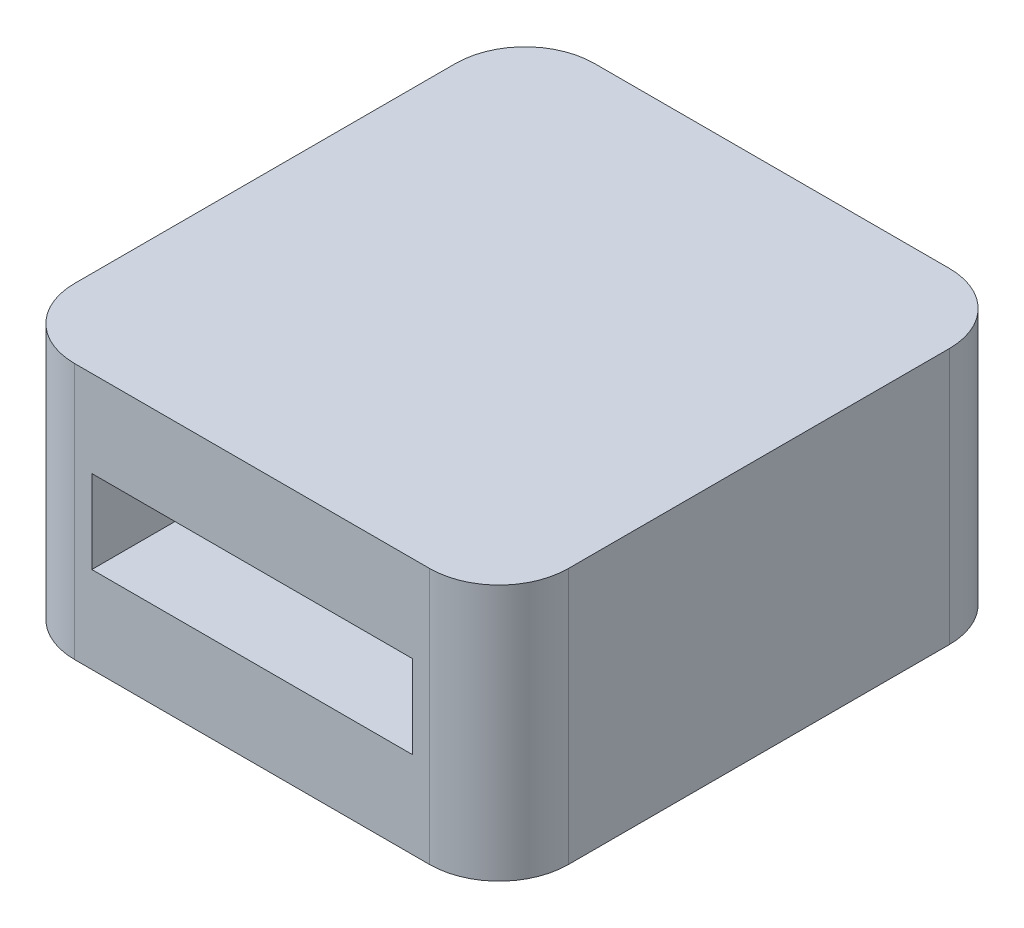
SolidWorks part; units mm, degrees
ref_plane "Front Plane" through (0, 0, 0) normal (0, 0, 1) x (1, 0, 0)
ref_plane "Top Plane" through (0, 0, 0) normal (0, 1, 0) x (1, 0, 0)
ref_plane "Right Plane" through (0, 0, 0) normal (1, 0, 0) x (0, 0, -1)
sketch "Profile Sketch" plane through (0, 0, 0) normal (0, 0, 1) x (1, 0, 0)
  line L0 (0, 1.2) -> (0, 3.7) construction
  line L1 (-4.625, -1.2) -> (4.625, -1.2)
  line L2 (-4.625, -1.2) -> (-4.625, 1.2)
  line L3 (-4.625, 1.2) -> (4.625, 1.2)
  line L4 (4.625, -1.2) -> (4.625, 1.2)
  line L5 (-4.625, -1.2) -> (4.625, 1.2) construction
  line L6 (-4.625, 1.2) -> (4.625, -1.2) construction
  line L7 (-7.125, -3.7) -> (7.125, -3.7)
  line L8 (-7.125, -3.7) -> (-7.125, 3.7)
  line L9 (-7.125, 3.7) -> (7.125, 3.7)
  line L10 (7.125, -3.7) -> (7.125, 3.7)
  line L11 (-7.125, -3.7) -> (7.125, 3.7) construction
  line L12 (-7.125, 3.7) -> (7.125, -3.7) construction
  line L13 (-4.625, 0) -> (-7.125, 0) construction
  point P0 (0, 0)
  point P6 (0, 0)
  dimension "D1" = 9.25
  dimension "D2" = 2.5
  dimension "D3" = 2.4
extrude "Profile Extrude" add sketch "Profile Sketch" along normal blind 15
fillet "Corner Fillets" radius 2 4 edges at (-7.125, 0, 0) (7.125, 0, 0) (7.125, 0, 15) (-7.125, 0, 15)
